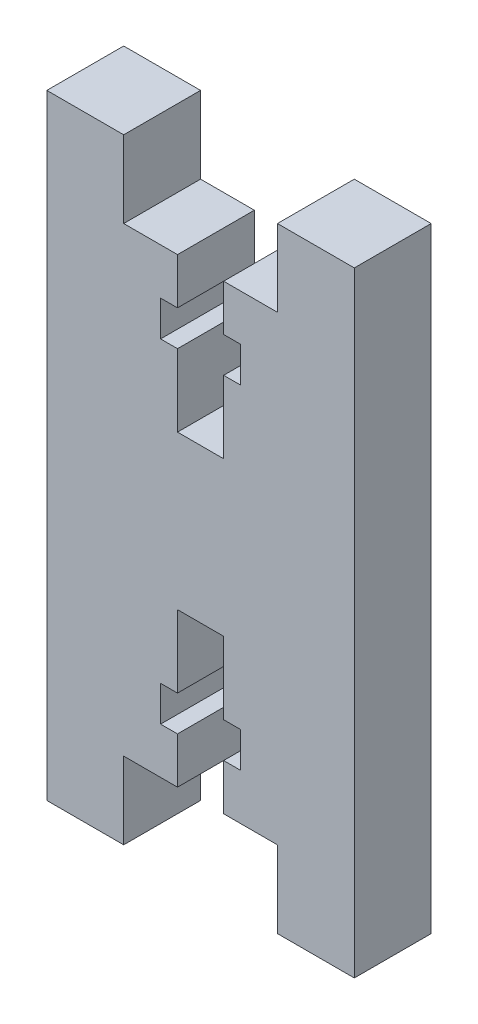
SolidWorks part; units mm, degrees
ref_plane "Front Plane" through (0, 0, 0) normal (0, 0, 1) x (1, 0, 0)
ref_plane "Top Plane" through (0, 0, 0) normal (0, 1, 0) x (1, 0, 0)
ref_plane "Right Plane" through (0, 0, 0) normal (1, 0, 0) x (0, 0, -1)
sketch "Sketch1" plane through (0, 0, 0) normal (0, 0, 1) x (1, 0, 0)
  line L1 (0, 0) -> (20, 0) construction
  line L3 (0, 30) -> (20, 30) construction
  line L8 (10, 30) -> (10, 38.7792) construction
  line L9 (11.5, 30) -> (15, 30)
  line L10 (15, 35) -> (20, 35)
  line L12 (15, 35) -> (15, 30)
  line L13 (8.5, 30) -> (5, 30)
  line L14 (5, 30) -> (5, 35)
  line L15 (5, 35) -> (0, 35)
  line L17 (11.5, 30) -> (8.5, 30) construction
  line L18 (8.5, 30) -> (8.5, 27)
  line L19 (8.5, 24.7) -> (7.4, 24.7)
  line L20 (12.6, 27) -> (12.6, 24.7)
  line L21 (7.4, 27) -> (8.5, 27)
  line L22 (8.5, 24.7) -> (8.5, 20)
  line L23 (8.5, 20) -> (11.5, 20)
  line L24 (11.5, 20) -> (11.5, 24.7)
  line L25 (11.5, 27) -> (12.6, 27)
  line L26 (7.4, 24.7) -> (7.4, 27)
  line L27 (12.6, 24.7) -> (11.5, 24.7)
  line L28 (11.5, 27) -> (11.5, 30)
  line L29 (10, 20) -> (10, 30) construction
  line L30 (10, 0) -> (10, 11.2208) construction
  line L31 (8.5, 0) -> (5, 0)
  line L32 (5, -5) -> (0, -5)
  line L33 (0, -5) -> (0, 0)
  line L34 (5, -5) -> (5, 0)
  line L35 (11.5, 0) -> (15, 0)
  line L36 (15, 0) -> (15, -5)
  line L37 (15, -5) -> (20, -5)
  line L38 (20, -5) -> (20, 0)
  line L39 (8.5, 0) -> (11.5, 0) construction
  line L40 (11.5, 0) -> (11.5, 3)
  line L41 (11.5, 5.3) -> (12.6, 5.3)
  line L42 (7.4, 3) -> (7.4, 5.3)
  line L43 (12.6, 3) -> (11.5, 3)
  line L44 (11.5, 5.3) -> (11.5, 10)
  line L45 (11.5, 10) -> (8.5, 10)
  line L46 (8.5, 10) -> (8.5, 5.3)
  line L47 (8.5, 3) -> (7.4, 3)
  line L48 (12.6, 5.3) -> (12.6, 3)
  line L49 (7.4, 5.3) -> (8.5, 5.3)
  line L50 (8.5, 3) -> (8.5, 0)
  line L51 (10, 10) -> (10, 0) construction
  line L52 (0, 35) -> (0, 0)
  line L53 (20, 0) -> (20, 35)
  point P11 (10, 0)
  dimension "D1" = 30
  dimension "D3" = 10
  dimension "D4" = 5
  dimension "D5" = 5
  dimension "D6" = 5.2
  dimension "D7" = 3
  dimension "D8" = 2.3
  dimension "D9" = 3
  dimension "D10" = 10
  dimension "D11" = 10
  dimension "D12" = 5
  dimension "D13" = 5
  dimension "D14" = 5.2
  dimension "D15" = 3
  dimension "D16" = 2.3
  dimension "D17" = 3
  dimension "D18" = 10
extrude "Boss-Extrude1" add sketch "Sketch1" along normal blind 5
